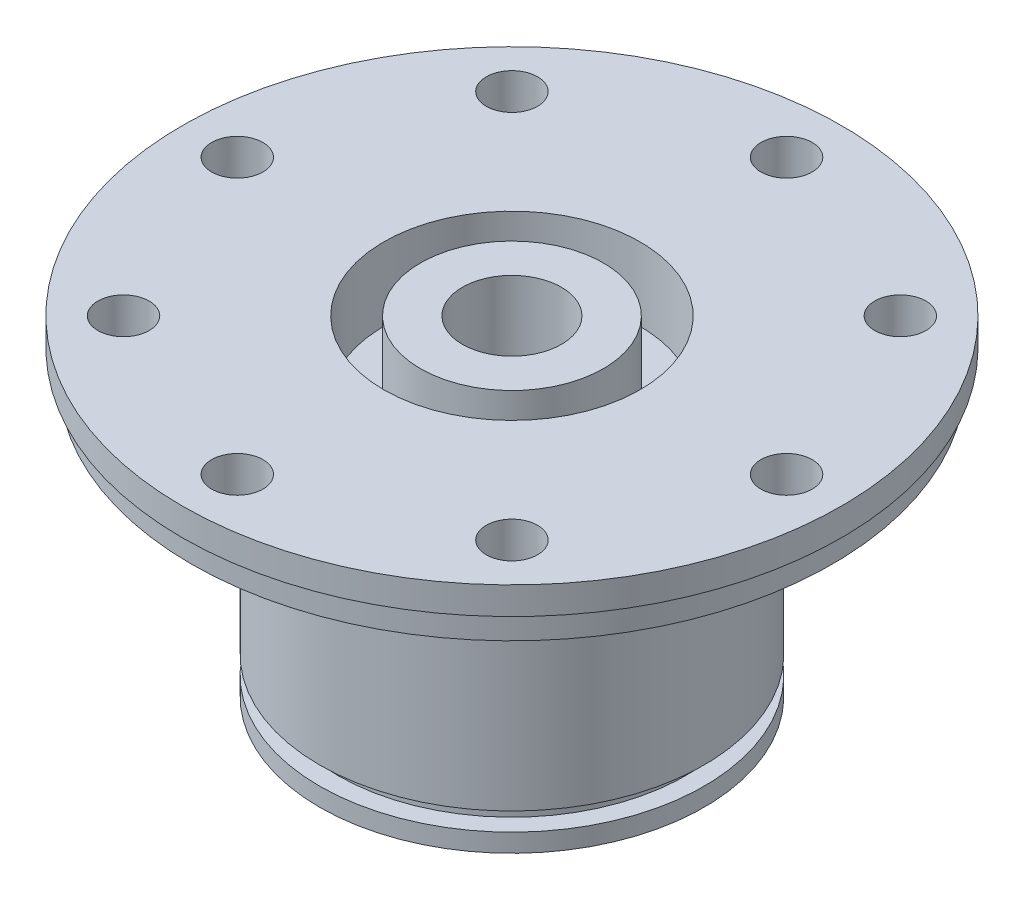
SolidWorks part; units mm, degrees
ref_plane "Front Plane" through (0, 0, 0) normal (0, 0, 1) x (1, 0, 0)
ref_plane "Top Plane" through (0, 0, 0) normal (0, 1, 0) x (1, 0, 0)
ref_plane "Right Plane" through (0, 0, 0) normal (1, 0, 0) x (0, 0, -1)
sketch "Sketch1" plane through (0, 0, 0) normal (0, 1, 0) x (1, 0, 0)
  circle A0 centre (0, 0) radius 18
  dimension "D1" = 36
extrude "Boss-Extrude1" add sketch "Sketch1" along normal blind 1.5
sketch "Sketch2" plane through (0, 0, 0) normal (0, -1, 0) x (1, 0, 0)
  circle A0 centre (0, 0) radius 17.5
  dimension "D1" = 35
extrude "Boss-Extrude2" add sketch "Sketch2" along normal blind 1.5
sketch "Sketch3" plane through (0, -1.5, 0) normal (0, -1, 0) x (1, 0, 0)
  circle A0 centre (0, 0) radius 12
  dimension "D1" = 24
extrude "Boss-Extrude3" add sketch "Sketch3" along normal blind 1
sketch "Sketch4" plane through (0, -2.5, 0) normal (0, -1, 0) x (1, 0, 0)
  circle A0 centre (0, 0) radius 10.5
  dimension "D1" = 21
extrude "Boss-Extrude4" add sketch "Sketch4" along normal blind 12
sketch "Sketch5" plane through (0, -14.5, 0) normal (0, -1, 0) x (1, 0, 0)
  circle A0 centre (0, 0) radius 9.5
  dimension "D1" = 19
extrude "Boss-Extrude5" add sketch "Sketch5" along normal blind 1
sketch "Sketch6" plane through (0, -15.5, 0) normal (0, -1, 0) x (1, 0, 0)
  circle A0 centre (0, 0) radius 10.5 construction
  circle A1 centre (0, 0) radius 10.5
extrude "Boss-Extrude6" add sketch "Sketch6" along normal blind 1
sketch "Sketch7" plane through (0, 0, 0) normal (0, 0, 1) x (1, 0, 0)
  line L0 (0, -16.5) -> (0, 1.5) construction
  line L1 (-10.5, -16.5) -> (10.5, -16.5) construction
  line L2 (18, 1.5) -> (-18, 1.5) construction
  line L3 (-8.5, -16.5) -> (0, -16.5)
  line L4 (0, -16.5) -> (0, -8)
  arc A0 (0, -8) -> (-8.5, -16.5) centre (0, -16.5) ccw
  dimension "D1" = 17
revolve "Cut-Revolve1" cut sketch "Sketch7" angle 360 about L0
sketch "Sketch8" plane through (0, 1.5, 0) normal (0, 1, 0) x (1, 0, 0)
  circle A0 centre (0, 0) radius 2.705
  dimension "D1" = 5.41
extrude "Cut-Extrude1" cut sketch "Sketch8" against normal through all
sketch "Sketch9" plane through (0, 1.5, 0) normal (0, 1, 0) x (1, 0, 0)
  circle A0 centre (0, 0) radius 5
  circle A1 centre (0, 0) radius 7
  dimension "D1" = 10
  dimension "D2" = 14
extrude "Cut-Extrude3" cut sketch "Sketch9" against normal up to surface (4 mm away) up to face at (0, -2.5, -10.5)
sketch "Sketch10" plane through (0, 1.5, 0) normal (0, 1, 0) x (1, 0, 0)
  arc A0 (-1.3985, 14.9347) -> (1.3985, 14.9347) centre (0, 0) ccw
  circle A1 centre (0, 15) radius 1.4
  dimension "D1" = 2.8
  dimension "D2" = 30
extrude "Cut-Extrude4" cut sketch "Sketch10" against normal blind 5 contours A1
pattern_circular "CirPattern1" count 8 over 360 about axis through (0, 0, 0) along (0, 1, 0) of "Cut-Extrude4"
